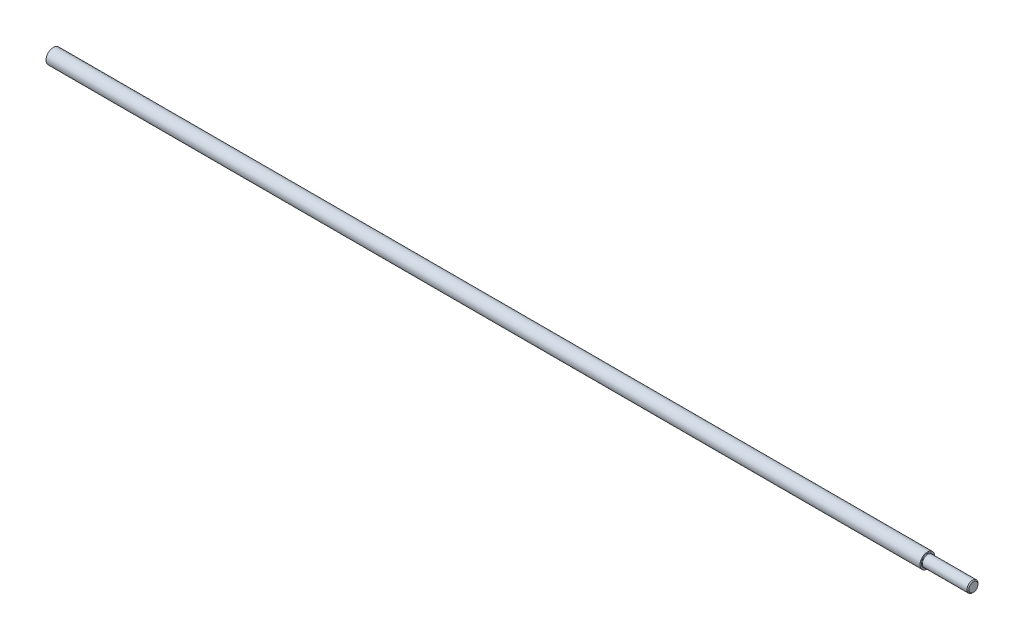
SolidWorks part; units mm, degrees
ref_plane "Front Plane" through (0, 0, 0) normal (0, 0, 1) x (1, 0, 0)
ref_plane "Top Plane" through (0, 0, 0) normal (0, 1, 0) x (1, 0, 0)
ref_plane "Right Plane" through (0, 0, 0) normal (1, 0, 0) x (0, 0, -1)
sketch "Sketch1" plane through (0, 0, 0) normal (0, 0, 1) x (1, 0, 0)
  line L0 (0, 4) -> (0, 0)
  line L1 (0, 0) -> (500, 0)
  line L2 (500, 0) -> (500, 2.5)
  line L3 (500, 2.5) -> (499.5, 3)
  line L4 (499.5, 3) -> (475.3, 3)
  line L5 (475, 3.3) -> (475, 4)
  line L6 (475, 4) -> (0, 4)
  line L7 (0, 0) -> (500, 0) construction
  arc A0 (475.3, 3) -> (475, 3.3) centre (475.3, 3.3) cw
revolve "Revolve1" add sketch "Sketch1" angle 360 about L7
